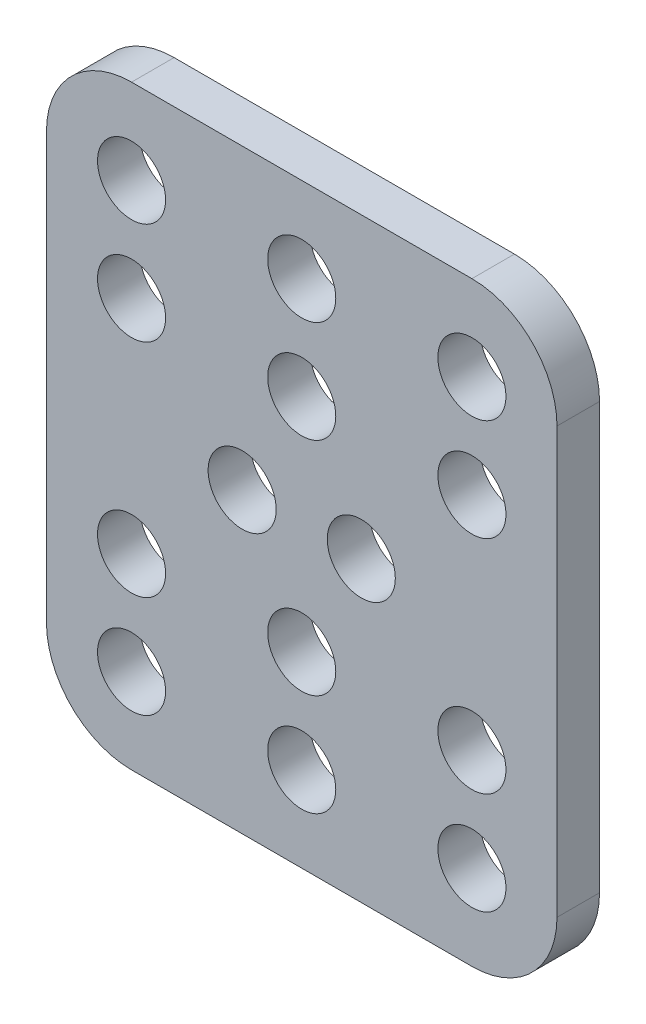
SolidWorks part; units mm, degrees
ref_plane "Front Plane" through (0, 0, 0) normal (0, 0, 1) x (1, 0, 0)
ref_plane "Top Plane" through (0, 0, 0) normal (0, 1, 0) x (1, 0, 0)
ref_plane "Right Plane" through (0, 0, 0) normal (1, 0, 0) x (0, 0, -1)
sketch "Sketch1" plane through (0, 0, 0) normal (0, 0, 1) x (1, 0, 0)
  line L1 (-20, 35) -> (20, 35)
  line L2 (-30, 25) -> (-30, -25)
  line L3 (-20, -35) -> (20, -35)
  line L4 (30, 25) -> (30, -25)
  circle A0 centre (7, 0) radius 4
  circle A1 centre (-7, 0) radius 4
  circle A2 centre (-20, 25) radius 4
  arc A3 (-30, -25) -> (-20, -35) centre (-20, -25) ccw
  arc A4 (20, -35) -> (30, -25) centre (20, -25) ccw
  arc A5 (20, 35) -> (30, 25) centre (20, 25) cw
  arc A6 (-20, 35) -> (-30, 25) centre (-20, 25) ccw
  circle A7 centre (20, 25) radius 4
  circle A8 centre (-20, -25) radius 4
  circle A9 centre (20, -25) radius 4
  circle A10 centre (0, -25) radius 4
  circle A11 centre (0, -13) radius 4
  circle A12 centre (0, 25) radius 4
  circle A13 centre (-20, -13) radius 4
  circle A14 centre (20, -13) radius 4
  circle A15 centre (-20, 13) radius 4
  circle A16 centre (0, 13) radius 4
  circle A17 centre (20, 13) radius 4
  point P0 (0, 0)
  point P15 (-30, -35)
  point P20 (30, 35)
  point P23 (-30, 35)
  dimension "D3" = 7
  dimension "D5" = 10
  dimension "D7" = 10
  dimension "D9" = 12
  dimension "D1" = 70
  dimension "D2" = 60
  dimension "D4" = 7
  dimension "D6" = 10
  dimension "D8" = 10
  dimension "D10" = 12
extrude "Boss-Extrude1" add sketch "Sketch1" along normal blind 5
